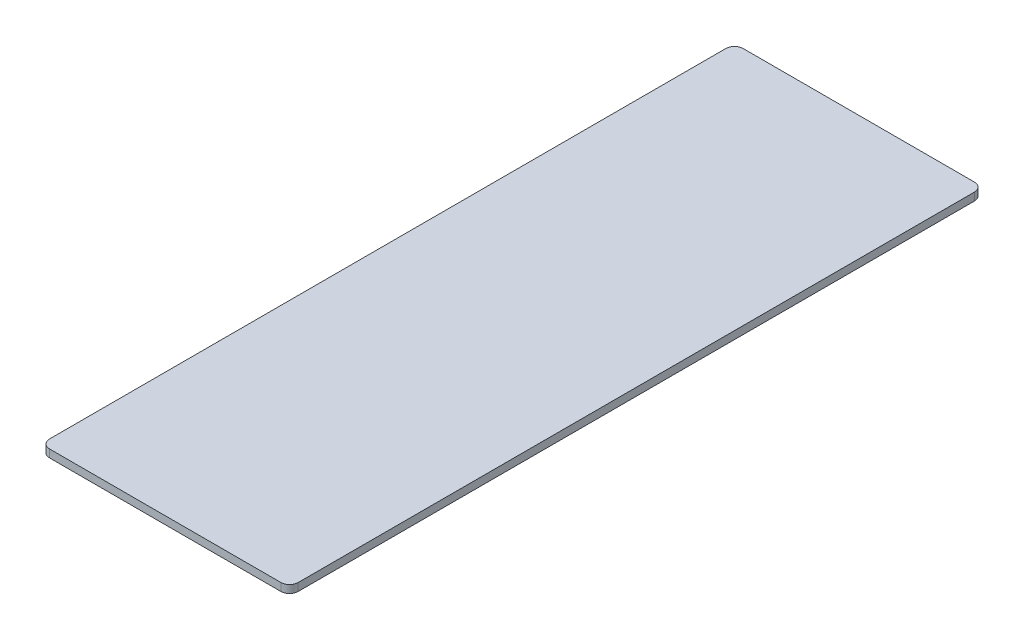
SolidWorks part; units mm, degrees
material "Acrylic (Medium-high impact)"
ref_plane "Front Plane" through (0, 0, 0) normal (0, 0, 1) x (1, 0, 0)
ref_plane "Top Plane" through (0, 0, 0) normal (0, 1, 0) x (1, 0, 0)
ref_plane "Right Plane" through (0, 0, 0) normal (1, 0, 0) x (0, 0, -1)
sketch "Sketch1" plane through (0, 0, 0) normal (0, 1, 0) x (1, 0, 0)
  line L1 (0, 0) -> (143.4, 0)
  line L2 (0, 0) -> (0, 400)
  line L3 (0, 400) -> (143.4, 400)
  line L4 (143.4, 0) -> (143.4, 400)
  dimension "D1" = 143.4
  dimension "D2" = 400
extrude "Boss-Extrude1" add sketch "Sketch1" along normal blind 4.5
fillet "Fillet1" radius 5 4 edges at (0, 2.25, -400) (143.4, 2.25, -400) (0, 2.25, 0) (143.4, 2.25, 0)
